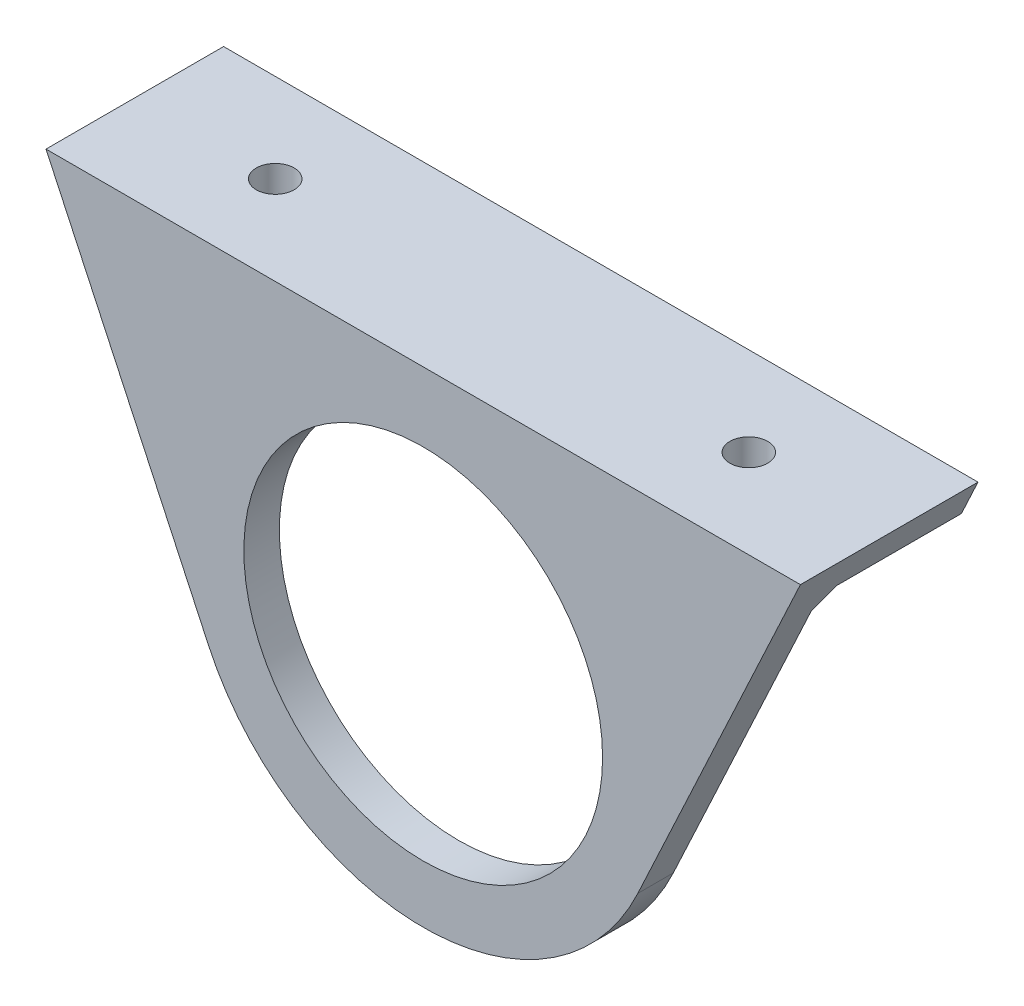
SolidWorks part; units mm, degrees
ref_plane "正面" through (0, 0, 0) normal (0, 0, 1) x (1, 0, 0)
ref_plane "平面" through (0, 0, 0) normal (0, 1, 0) x (1, 0, 0)
ref_plane "右側面" through (0, 0, 0) normal (1, 0, 0) x (0, 0, -1)
sketch "ｽｹｯﾁ1" plane through (0, 0, 0) normal (0, 0, 1) x (1, 0, 0)
  line L0 (-18.1262, -8.4524) -> (-31.86, 21)
  line L1 (-31.86, 21) -> (31.86, 21)
  line L2 (18.1262, -8.4524) -> (31.86, 21)
  circle A0 centre (0, 0) radius 15.15
  arc A1 (-18.1262, -8.4524) -> (18.1262, -8.4524) centre (0, 0) ccw
  dimension "D1" = 30.3
  dimension "D2" = 40
  dimension "D3" = 65
  dimension "D4" = 21
extrude "ﾎﾞｽ - 押し出し1" add sketch "ｽｹｯﾁ1" along normal blind 15
sketch "ｽｹｯﾁ2" plane through (0, 0, 0) normal (1, 0, 0) x (0, 0, -1)
  line L0 (0, -8.4524) -> (0, 21) construction
  line L1 (0, 18) -> (-12, 18)
  line L2 (0, 18) -> (0, -20)
  line L3 (0, -20) -> (-12, -20)
  line L4 (-12, 18) -> (-12, -20)
  line L5 (-15, -20) -> (0, -20) construction
  line L6 (-15, -8.4524) -> (-15, 21) construction
  line L7 (-15, 21) -> (0, 21) construction
  dimension "D1" = 3
  dimension "D2" = 3
extrude "ｶｯﾄ - 押し出し1" cut sketch "ｽｹｯﾁ2" against normal mid plane 70
sketch "ｽｹｯﾁ3" plane through (0, 21, 0) normal (0, 1, 0) x (1, 0, 0)
  line L0 (-31.86, -7.5) -> (-20, -7.5) construction
  line L1 (-31.86, -15) -> (-31.86, 0) construction
  line L2 (-20, -7.5) -> (20, -7.5) construction
  line L3 (20, -7.5) -> (31.86, -7.5) construction
  line L4 (31.86, -15) -> (31.86, 0) construction
  circle A0 centre (-20, -7.5) radius 1.6
  circle A1 centre (20, -7.5) radius 1.6
  dimension "D1" = 3.2
  dimension "D2" = 40
extrude "ｶｯﾄ - 押し出し2" cut sketch "ｽｹｯﾁ3" against normal up to next
chamfer "面取り1" distance 1.5 angle 45 1 edges at (0, 18, 12)
